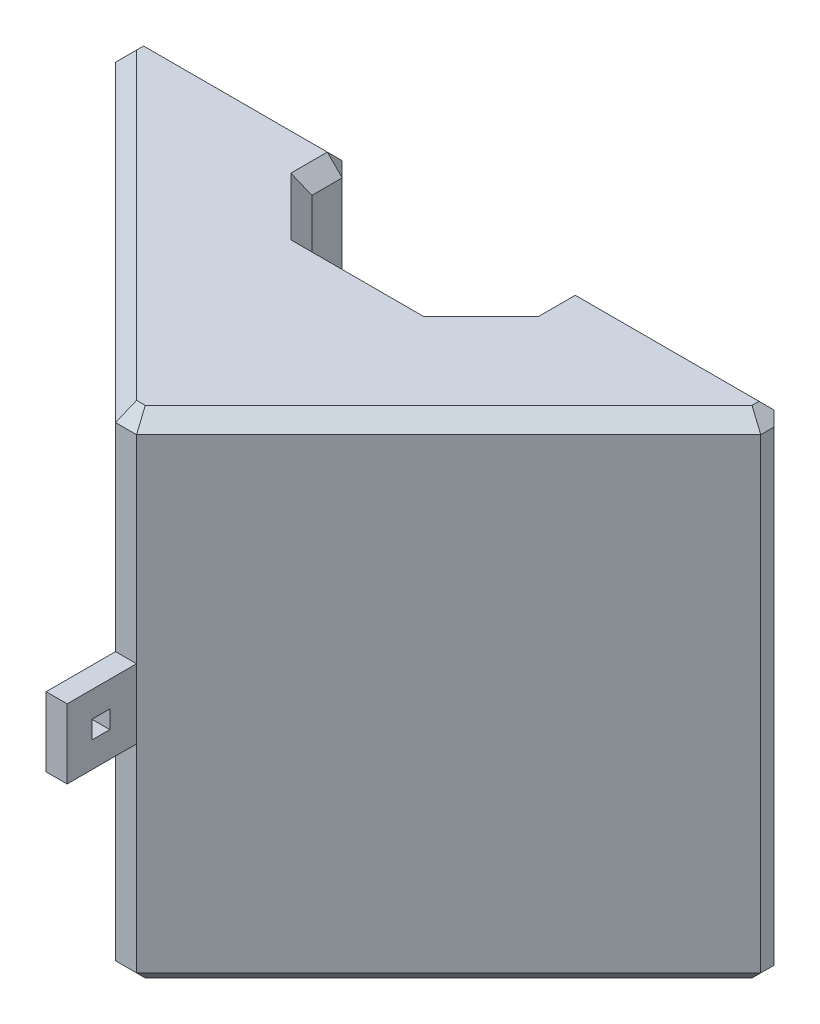
SolidWorks part; units mm, degrees
ref_plane "Front" through (0, 0, 0) normal (0, 0, 1) x (1, 0, 0)
ref_plane "Top" through (0, 0, 0) normal (0, 1, 0) x (1, 0, 0)
ref_plane "Right" through (0, 0, 0) normal (1, 0, 0) x (0, 0, -1)
sketch "Sketch4" plane through (0, 0, 0) normal (0, 1, 0) x (1, 0, 0)
  line L0 (0, 0) -> (70.7107, 0)
  line L1 (70.7107, 0) -> (35.3553, -35.3553)
  line L2 (35.3553, -35.3553) -> (0, 0)
  dimension "D1" = 50
extrude "Boss-Extrude1" add sketch "Sketch4" along normal blind 50
sketch "Sketch5" plane through (0, 0, 0) normal (0, -1, 0) x (1, 0, 0)
  line L0 (70.7107, 0) -> (0, 0) construction
  line L1 (39.9117, 11) -> (30.799, 11)
  line L2 (30.799, 11) -> (24.3553, 4.5563)
  line L3 (24.3553, 4.5563) -> (24.3553, -4.5563)
  line L4 (24.3553, -4.5563) -> (30.799, -11)
  line L5 (30.799, -11) -> (39.9117, -11)
  line L6 (39.9117, -11) -> (46.3553, -4.5563)
  line L7 (46.3553, -4.5563) -> (46.3553, 4.5563)
  line L8 (46.3553, 4.5563) -> (39.9117, 11)
  circle A0 centre (35.3553, 0) radius 11 construction
  dimension "D1" = 22
extrude "Cut-Extrude3" cut sketch "Sketch5" against normal through all
chamfer "Chamfer2" distance 4 angle 45 2 edges at (0, 25, 0) (70.7107, 25, 0)
chamfer "Chamfer3" distance 1.5 angle 45 17 edges at (27.5772, 50, 7.7782) (24.3553, 50, 2.2782) (13.5919, 50, 0) (24.3553, 25, 0) (27.5772, 0, 7.7782) (24.3553, 0, 2.2782) (13.5919, 0, 0) (2.8284, 25, 0) (43.1335, 50, 7.7782) (46.3553, 50, 2.2782) (57.1188, 50, 0) (46.3553, 25, 0) (43.1335, 0, 7.7782) (46.3553, 0, 2.2782) (57.1188, 0, 0) (67.8823, 25, 0) (35.3553, 25, 35.3553)
chamfer "Chamfer4" distance 1.5 angle 45 10 edges at (2.8284, 50, 2.1642) (18.5616, 50, 18.5616) (35.3553, 50, 34.2947) (52.1491, 50, 18.5616) (67.8823, 50, 2.1642) (2.8284, 0, 2.1642) (67.8823, 0, 2.1642) (52.1491, 0, 18.5616) (35.3553, 0, 34.2947) (18.5616, 0, 18.5616)
sketch "Sketch6" plane through (0, 0, 34.2947) normal (0, 0, 1) x (1, 0, 0)
  line L0 (34.2947, 1.5) -> (34.2947, 48.5) construction
  line L1 (34.2947, 28.5) -> (36.416, 28.5)
  line L2 (34.2947, 28.5) -> (34.2947, 21.5)
  line L3 (34.2947, 21.5) -> (36.416, 21.5)
  line L4 (36.416, 28.5) -> (36.416, 21.5)
  line L5 (36.416, 48.5) -> (36.416, 1.5) construction
  point P8 (36.416, 25)
  dimension "D1" = 7
extrude "Boss-Extrude2" add sketch "Sketch6" along normal blind 7
sketch "Sketch7" plane through (36.416, 0, 0) normal (1, 0, 0) x (0, 0, -1)
  line L0 (-38.7947, 25) -> (-41.2947, 25) construction
  line L1 (-38.7947, 25.9) -> (-36.9947, 25.9)
  line L2 (-38.7947, 25.9) -> (-38.7947, 24.1)
  line L3 (-38.7947, 24.1) -> (-36.9947, 24.1)
  line L4 (-36.9947, 25.9) -> (-36.9947, 24.1)
  line L5 (-41.2947, 21.5) -> (-41.2947, 28.5) construction
  dimension "D1" = 1.8
  dimension "D2" = 2.5
extrude "Cut-Extrude4" cut sketch "Sketch7" against normal blind 7
